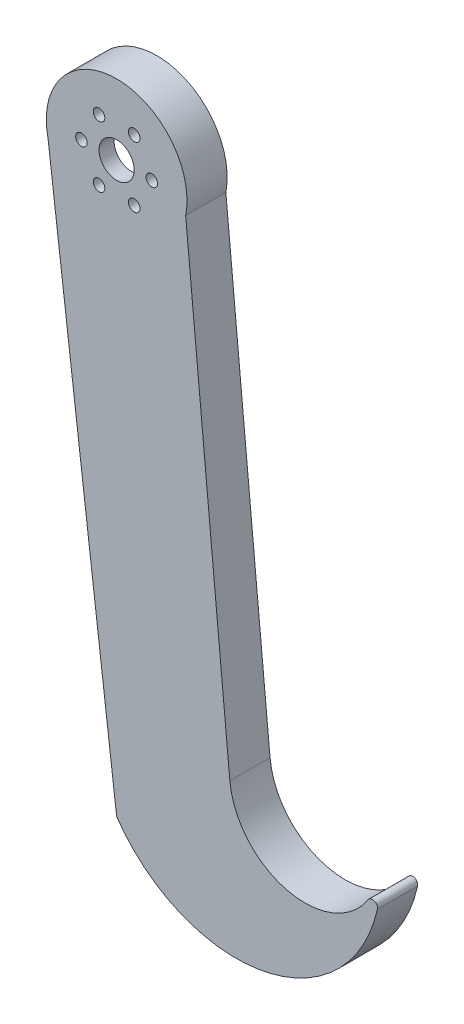
SolidWorks part; units mm, degrees
ref_plane "정면" through (0, 0, 0) normal (0, 0, 1) x (1, 0, 0)
ref_plane "윗면" through (0, 0, 0) normal (0, 1, 0) x (1, 0, 0)
ref_plane "우측면" through (0, 0, 0) normal (1, 0, 0) x (0, 0, -1)
sketch "스케치1" plane through (0, 0, 0) normal (0, 0, 1) x (1, 0, 0)
  circle A0 centre (0, 0) radius 14
  dimension "D1" = 28
extrude "보스-돌출1" add sketch "스케치1" along normal blind 8
sketch "스케치2" plane through (0, 0, 0) normal (0, 0, -1) x (-1, 0, 0)
  circle A0 centre (0, 0) radius 10.6
  dimension "D1" = 21.2
sketch "스케치3" plane through (0, 0, 8) normal (0, 0, 1) x (1, 0, 0)
  circle A0 centre (0, 0) radius 3.5
  dimension "D1" = 7
extrude "컷-돌출2" cut sketch "스케치3" against normal blind 10
sketch "스케치6" plane through (0, 0, 8) normal (0, 0, 1) x (1, 0, 0)
  line L0 (0, 0) -> (0, 18.4707) construction
  line L1 (-14, 37.9731) -> (-14, -35.8302) construction
  line L2 (14, 37.9731) -> (14, -35.8302) construction
  line L3 (13.7356, -2.7081) -> (22.5285, -95.7081)
  line L4 (-13.649, -3.1153) -> (0, -113.1153)
  arc A0 (22.5285, -95.7081) -> (52.4619, -94.2881) centre (37.4619, -94.2962) ccw
  circle A1 centre (0, 0) radius 14 construction
  arc A2 (0, -113.1153) -> (52.4619, -94.2881) centre (23.7903, -96.9007) ccw
  arc A3 (-13.649, -3.1153) -> (13.7356, -2.7081) centre (0, 0) ccw
  dimension "D3" = 15
  dimension "D1" = 93
  dimension "D2" = 110
extrude "보스-돌출3" add sketch "스케치6" against normal blind 8
extrude "컷-돌출3" cut sketch "스케치2" against normal blind 5
sketch "스케치7" plane through (0, 0, 5) normal (0, 0, -1) x (-1, 0, 0)
  circle A0 centre (7, 0) radius 1.15
  circle A1 centre (3.5, -6.0622) radius 1.15
  circle A2 centre (-3.5, -6.0622) radius 1.15
  circle A3 centre (-7, 0) radius 1.15
  circle A4 centre (-3.5, 6.0622) radius 1.15
  circle A5 centre (3.5, 6.0622) radius 1.15
  point P15 (0, 0)
  dimension "D1" = 2.3
  dimension "D2" = 7
  dimension "D3" = 6
extrude "컷-돌출4" cut sketch "스케치7" against normal blind 5
fillet "필렛1" radius 1 1 edges at (52.4619, -94.2881, 4)
fillet "필렛2" radius 1 1 edges at (0, -113.1153, 4)
